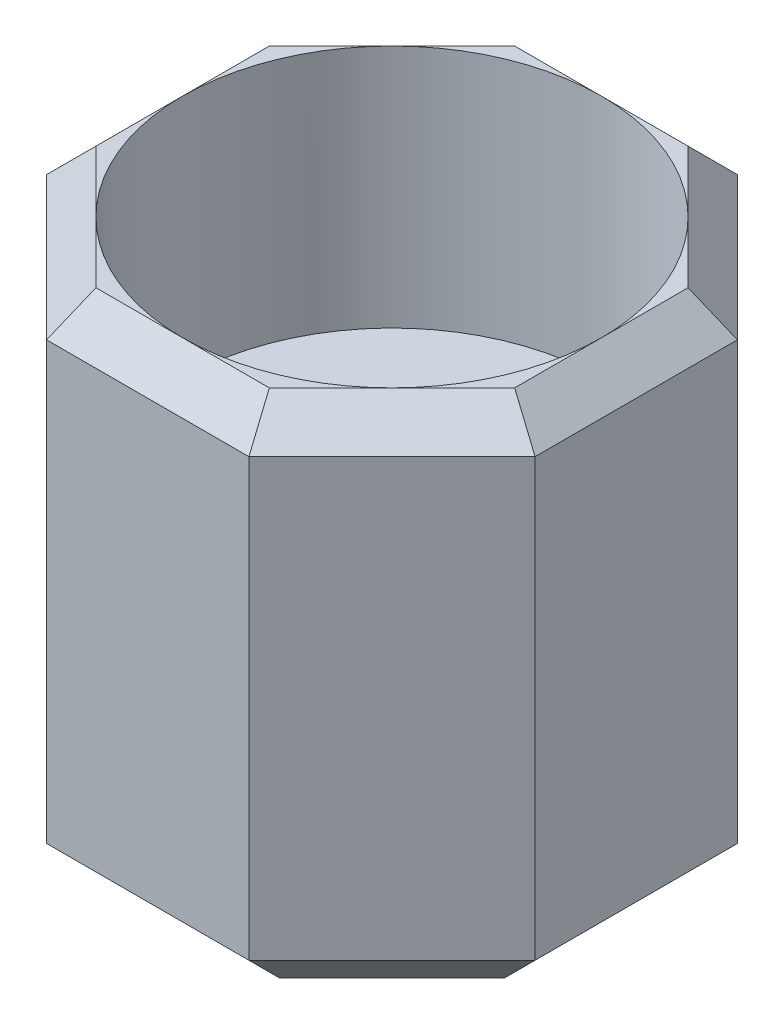
SolidWorks part; units mm, degrees
ref_plane "Спереди" through (0, 0, 0) normal (0, 0, 1) x (1, 0, 0)
ref_plane "Сверху" through (0, 0, 0) normal (0, 1, 0) x (1, 0, 0)
ref_plane "Справа" through (0, 0, 0) normal (1, 0, 0) x (0, 0, -1)
sketch "Эскиз1" plane through (0, 0, 0) normal (0, 1, 0) x (1, 0, 0)
  line L0 (-7, 2.8995) -> (-2.8995, 7)
  line L1 (-7, -7) -> (7, -7)
  line L2 (-7, -7) -> (-7, 7)
  line L3 (-7, 7) -> (7, 7)
  line L4 (7, -7) -> (7, 7)
  line L5 (-7, -7) -> (7, 7) construction
  line L6 (-7, 7) -> (7, -7) construction
  line L7 (2.8995, -7) -> (7, -2.8995)
  line L8 (-7, -2.8995) -> (-2.8995, -7)
  line L9 (2.8995, 7) -> (7, 2.8995)
  point P0 (0, 0)
  dimension "D1" = 14
  dimension "D2" = 14
  dimension "D3" = 14
  dimension "D4" = 14
extrude "Бобышка-Вытянуть1" add sketch "Эскиз1" along normal blind 15 contours L9 L3 L0 L2 L8 L1 L7 L4
chamfer "Фаска1" distance 1 angle 45 8 edges at (7, 15, 0) (4.9497, 15, 4.9497) (0, 15, 7) (-4.9497, 15, 4.9497) (-7, 15, 0) (-4.9497, 15, -4.9497) (0, 15, -7) (4.9497, 15, -4.9497)
chamfer "Фаска2" distance 1.5 angle 45 8 edges at (0, 0, -7) (-4.9497, 0, -4.9497) (-7, 0, 0) (-4.9497, 0, 4.9497) (0, 0, 7) (4.9497, 0, 4.9497) (7, 0, 0) (4.9497, 0, -4.9497)
sketch "Эскиз2" plane through (0, 15, 0) normal (0, 1, 0) x (1, 0, 0)
  circle A0 centre (0, 0) radius 6
  dimension "D1" = 12
extrude "Вырез-Вытянуть1" cut sketch "Эскиз2" against normal blind 7
sketch "Эскиз3" plane through (0, 0, 0) normal (0, -1, 0) x (1, 0, 0)
  circle A0 centre (0, 0) radius 3.5
  dimension "D1" = 7
extrude "Вырез-Вытянуть2" cut sketch "Эскиз3" against normal blind 4.5
sketch "Эскиз4" plane through (0, 4.5, 0) normal (0, -1, 0) x (1, 0, 0)
  circle A0 centre (0, 0) radius 1
  dimension "D1" = 2
extrude "Вырез-Вытянуть3" cut sketch "Эскиз4" against normal blind 1.5
chamfer "Фаска5" distance 1 angle 45 1 edges at (0, 6, -1)
